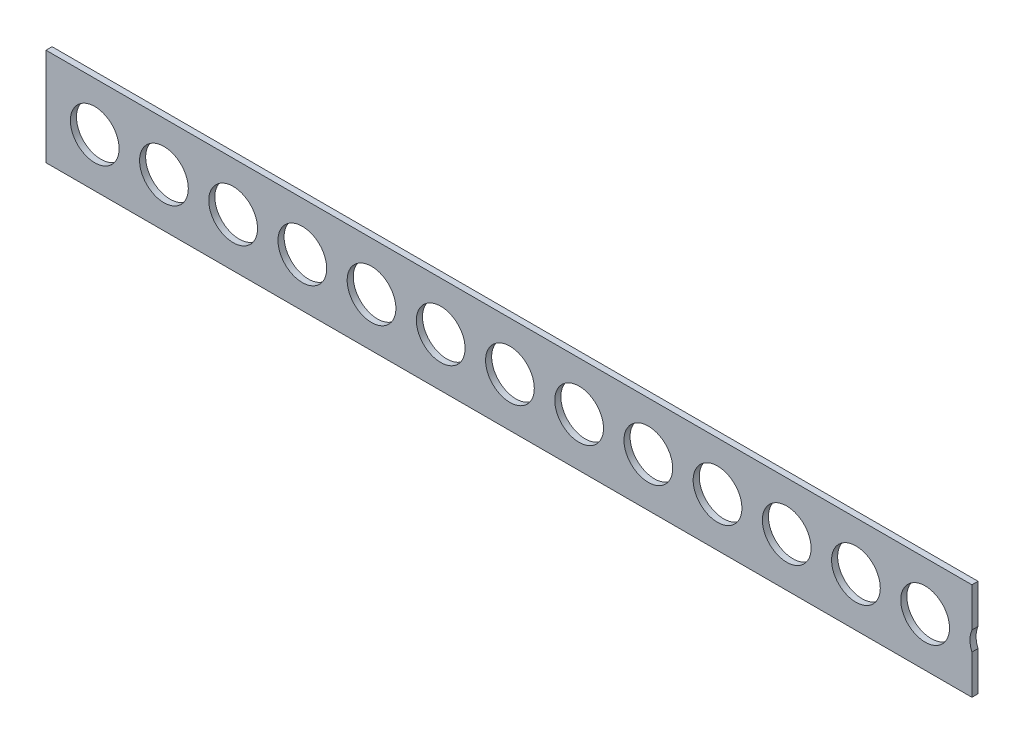
SolidWorks part; units mm, degrees
ref_plane "Front Plane" through (0, 0, 0) normal (0, 0, 1) x (1, 0, 0)
ref_plane "Top Plane" through (0, 0, 0) normal (0, 1, 0) x (1, 0, 0)
ref_plane "Right Plane" through (0, 0, 0) normal (1, 0, 0) x (0, 0, -1)
sketch "Sketch1" plane through (0, 0, 0) normal (0, 0, 1) x (1, 0, 0)
  line L0 (0, 0) -> (0, 50.8)
  line L1 (0, 50.8) -> (482.6, 50.8)
  line L2 (482.6, 50.8) -> (482.6, 0)
  line L3 (482.6, 0) -> (0, 0)
  dimension "D1" = 482.6
  dimension "D2" = 50.8
extrude "Boss-Extrude1" add sketch "Sketch1" along normal blind 3.175
sketch "Sketch2" plane through (0, 0, 3.175) normal (0, 0, 1) x (1, 0, 0)
  line L0 (482.6, 50.8) -> (0, 50.8) construction
  line L2 (0, 50.8) -> (0, 0) construction
  circle A0 centre (25.4, 25.4) radius 12.7
  dimension "D1" = 25.4
  dimension "D3" = 25.4
  dimension "D4" = 25.4
  dimension "D2" = 25.4
extrude "Cut-Extrude1" cut sketch "Sketch2" against normal through all
pattern_linear "LPattern1" count 15 spacing 36.068 along (1, 0, 0) of "Cut-Extrude1"
